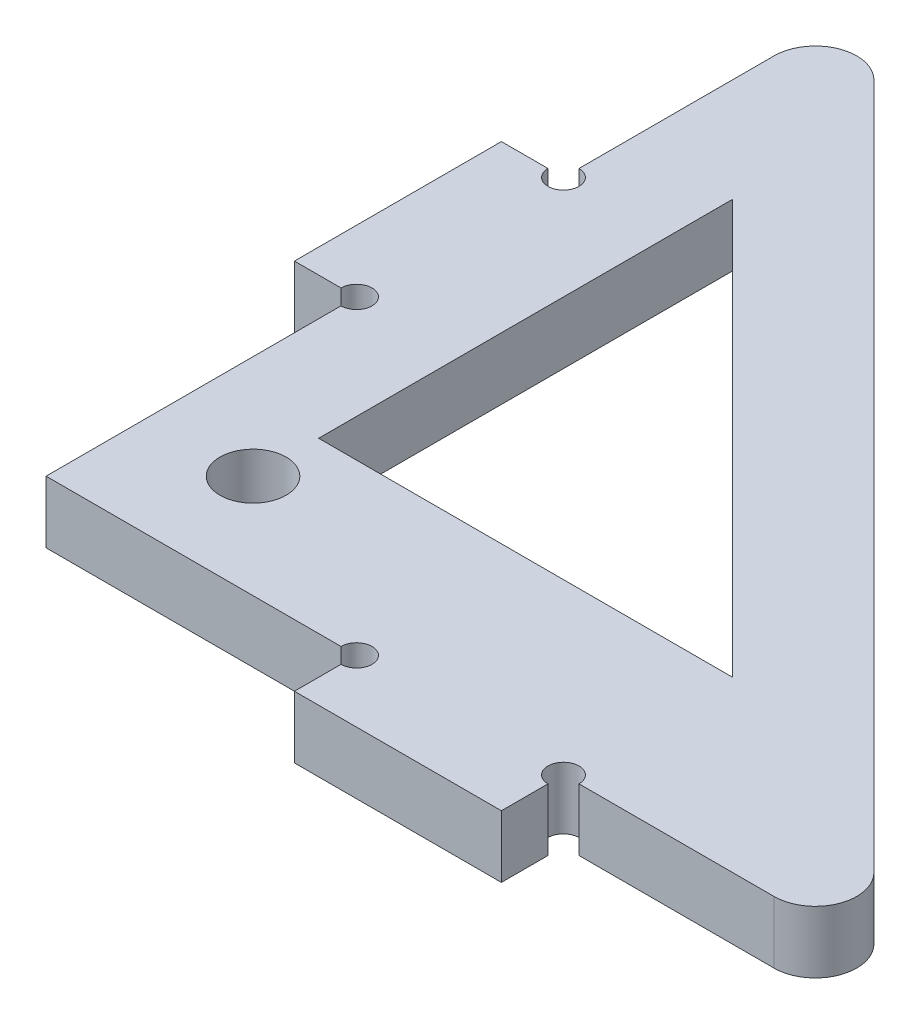
SolidWorks part; units mm, degrees
ref_plane "前视基准面" through (0, 0, 0) normal (0, 0, 1) x (1, 0, 0)
ref_plane "上视基准面" through (0, 0, 0) normal (0, 1, 0) x (1, 0, 0)
ref_plane "右视基准面" through (0, 0, 0) normal (1, 0, 0) x (0, 0, -1)
other "Configuration Table"
sketch "草图1" plane through (0, 0, 0) normal (0, 1, 0) x (1, 0, 0)
  line L0 (0, 0) -> (0, 40)
  line L1 (0, 40) -> (40, 0)
  line L2 (40, 0) -> (0, 0)
  line L3 (15, 0) -> (15, -3)
  line L4 (15, -3) -> (25, -3)
  line L5 (25, -3) -> (25, 0)
  line L6 (20, -3) -> (20, 0) construction
  line L7 (0, 0) -> (20, 20) construction
  line L8 (-3, 20) -> (0, 20) construction
  line L9 (-3, 25) -> (0, 25)
  line L10 (-3, 15) -> (-3, 25)
  line L11 (0, 15) -> (-3, 15)
  dimension "D1" = 40
  dimension "D2" = 40
  dimension "D3" = 10
  dimension "D4" = 3
  dimension "D5" = 20
  dimension "D6" = 45
extrude "凸台-拉伸1" add sketch "草图1" along normal blind 3 contours L2 L1 L0 | L11 L0 L9 L10 | L4 L5 L2 L3
sketch "草图2" plane through (0, 3, 0) normal (0, 1, 0) x (1, 0, 0)
  line L0 (15, 0) -> (0, 0) construction
  line L1 (0, 0) -> (0, 15) construction
  line L2 (5, 28.1698) -> (5, 8.1698)
  line L3 (5, 8.1698) -> (25, 8.1698)
  line L4 (25, 8.1698) -> (5, 28.1698)
  line L5 (0, 40) -> (40, 0) construction
  circle A0 centre (5, 5) radius 1.6
  circle A1 centre (0, 25) radius 0.75
  circle A2 centre (0, 15) radius 0.75
  circle A3 centre (15, 0) radius 0.75
  circle A4 centre (25, 0) radius 0.75
  dimension "D1" = 3.2
  dimension "D4" = 1.5
  dimension "D2" = 5
  dimension "D3" = 5
  dimension "D5" = 20
extrude "切除-拉伸1" cut sketch "草图2" against normal through all
fillet "圆角1" radius 2 2 edges at (40, 1.5, 0) (0, 1.5, -40)
